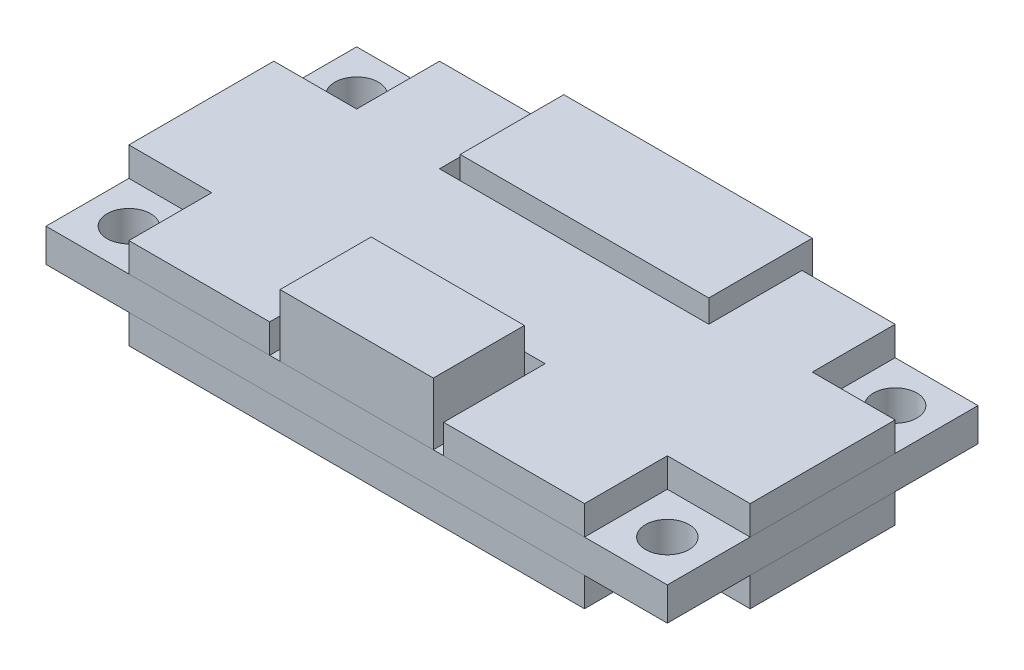
SolidWorks part; units mm, degrees
ref_plane "Front Plane" through (0, 0, 0) normal (0, 0, 1) x (1, 0, 0)
ref_plane "Top Plane" through (0, 0, 0) normal (0, 1, 0) x (1, 0, 0)
ref_plane "Right Plane" through (0, 0, 0) normal (1, 0, 0) x (0, 0, -1)
sketch "Sketch1" plane through (0, 0, 0) normal (0, 1, 0) x (1, 0, 0)
  line L1 (-15, -7.5) -> (15, -7.5)
  line L2 (-15, -7.5) -> (-15, 7.5)
  line L3 (-15, 7.5) -> (15, 7.5)
  line L4 (15, -7.5) -> (15, 7.5)
  line L5 (-15, -7.5) -> (15, 7.5) construction
  line L6 (-15, 7.5) -> (15, -7.5) construction
  line L7 (-13, -5.5) -> (13, -5.5) construction
  line L8 (-13, -5.5) -> (-13, 5.5) construction
  line L9 (-13, 5.5) -> (13, 5.5) construction
  line L10 (13, -5.5) -> (13, 5.5) construction
  line L11 (-13, -5.5) -> (13, 5.5) construction
  line L12 (-13, 5.5) -> (13, -5.5) construction
  circle A0 centre (13, 5.5) radius 1.05
  circle A1 centre (13, -5.5) radius 1.05
  circle A2 centre (-13, -5.5) radius 1.05
  circle A3 centre (-13, 5.5) radius 1.05
  point P0 (0, 0)
  point P6 (0, 0)
  dimension "D5" = 2.1
  dimension "D1" = 30
  dimension "D2" = 15
  dimension "D3" = 26
  dimension "D4" = 11
extrude "Boss-Extrude1" add sketch "Sketch1" against normal blind 1.6
sketch "Sketch2" plane through (0, 0, 0) normal (0, 1, 0) x (1, 0, 0)
  line L0 (0, 0) -> (0, 3.5) construction
  line L1 (-6, 8.5) -> (6, 8.5)
  line L2 (-6, 8.5) -> (-6, 3.5)
  line L3 (-6, 3.5) -> (6, 3.5)
  line L4 (6, 8.5) -> (6, 3.5)
  line L5 (-15, -7.5) -> (15, -7.5) construction
  dimension "D1" = 16
  dimension "D2" = 5
  dimension "D3" = 12
extrude "Boss-Extrude2" add sketch "Sketch2" along normal blind 2 separate body
sketch "Sketch3" plane through (0, 0, 0) normal (0, 1, 0) x (1, 0, 0)
  line L0 (-15, -7.5) -> (15, -7.5) construction
  line L1 (-3.7, -3.1) -> (3.7, -3.1)
  line L2 (-3.7, -3.1) -> (-3.7, -7.5)
  line L3 (-3.7, -7.5) -> (3.7, -7.5)
  line L4 (3.7, -3.1) -> (3.7, -7.5)
  line L5 (0, 0) -> (0, -3.1) construction
  dimension "D1" = 4.4
  dimension "D2" = 7.4
extrude "Boss-Extrude3" add sketch "Sketch3" along normal blind 3 separate body
sketch "Sketch4" plane through (0, -1.6, 0) normal (0, -1, 0) x (1, 0, 0)
  line L0 (-11, 5.5) -> (-15, 5.5) construction
  line L1 (-15, 7.5) -> (-11, 7.5) construction
  line L2 (-15, 7.5) -> (-15, 3.5) construction
  line L3 (-15, 3.5) -> (-11, 3.5)
  line L4 (-11, 7.5) -> (-11, 3.5)
  line L5 (0, 0) -> (-15, 0) construction
  line L6 (-15, -7.5) -> (-15, 7.5) construction
  line L7 (-11, -7.5) -> (-11, -3.5)
  line L8 (-15, 7.5) -> (15, 7.5) construction
  line L9 (0, 7.5) -> (0, 0) construction
  line L10 (-15, -3.5) -> (-11, -3.5)
  line L11 (-15, -3.5) -> (-15, 3.5)
  line L12 (15, -3.5) -> (11, -3.5)
  line L13 (11, -7.5) -> (11, -3.5)
  line L14 (15, -3.5) -> (15, 3.5)
  line L15 (11, 7.5) -> (11, 3.5)
  line L16 (15, 3.5) -> (11, 3.5)
  line L17 (-11, 7.5) -> (11, 7.5)
  line L18 (11, -7.5) -> (-11, -7.5)
  circle A0 centre (-13, 5.5) radius 1.05 construction
  point P7 (-13, 5.5)
extrude "Boss-Extrude4" add sketch "Sketch4" along normal blind 1.4 separate body
sketch "Sketch5" plane through (0, 0, 0) normal (0, 1, 0) x (1, 0, 0)
  line L8 (-6.5, 9) -> (-6.5, 3)
  line L9 (-6.5, 3) -> (6.5, 3)
  line L10 (6.5, 3) -> (6.5, 9)
  line L11 (6.5, 9) -> (-6.5, 9)
  line L12 (-11, -3.5) -> (-11, -7.5)
  line L13 (-15, -3.5) -> (-11, -3.5)
  line L14 (-15, 3.5) -> (-15, -3.5)
  line L15 (-11, 3.5) -> (-15, 3.5)
  line L16 (-11, 7.5) -> (-11, 3.5)
  line L17 (11, 7.5) -> (-11, 7.5)
  line L18 (11, 3.5) -> (11, 7.5)
  line L19 (15, 3.5) -> (11, 3.5)
  line L20 (15, -3.5) -> (15, 3.5)
  line L21 (11, -3.5) -> (15, -3.5)
  line L22 (11, -7.5) -> (11, -3.5)
  line L23 (-11, -7.5) -> (11, -7.5)
  line L24 (-11, -3.5) -> (-11, -7.5)
  line L25 (-15, -3.5) -> (-11, -3.5)
  line L26 (-15, 3.5) -> (-15, -3.5)
  line L27 (-11, 3.5) -> (-15, 3.5)
  line L28 (-11, 7.5) -> (-11, 3.5)
  line L29 (11, 7.5) -> (6.5, 7.5)
  line L30 (11, 3.5) -> (11, 7.5)
  line L31 (15, 3.5) -> (11, 3.5)
  line L32 (15, -3.5) -> (15, 3.5)
  line L33 (11, -3.5) -> (15, -3.5)
  line L34 (11, -7.5) -> (11, -3.5)
  line L35 (-11, -7.5) -> (-4.2, -7.5)
  line L36 (-6.5, 7.5) -> (-6.5, 3)
  line L37 (-6.5, 3) -> (6.5, 3)
  line L38 (6.5, 3) -> (6.5, 7.5)
  line L40 (-6.5, 7.5) -> (-11, 7.5)
  line L41 (4.2, -7.5) -> (11, -7.5)
  line L44 (-4.2, -2.6) -> (-4.2, -8)
  line L45 (-4.2, -8) -> (4.2, -8)
  line L46 (4.2, -8) -> (4.2, -2.6)
  line L47 (4.2, -2.6) -> (-4.2, -2.6)
  line L48 (-4.2, -2.6) -> (-4.2, -7.5)
  line L50 (4.2, -7.5) -> (4.2, -2.6)
  line L51 (4.2, -2.6) -> (-4.2, -2.6)
  dimension "D1" = 0
  dimension "D2" = 0.5
  dimension "D3" = 0.5
extrude "Boss-Extrude5" add sketch "Sketch5" along normal blind 1.4 separate body
